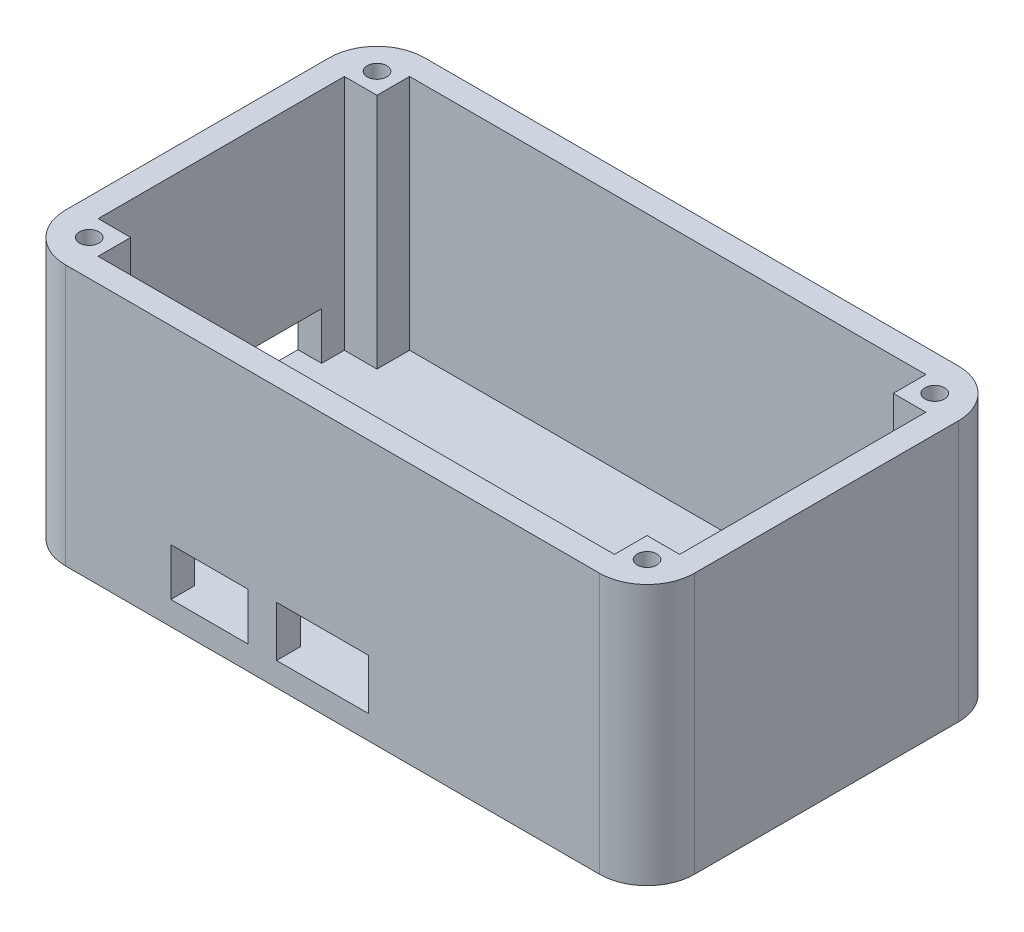
SolidWorks part; units mm, degrees
ref_plane "Front Plane" through (0, 0, 0) normal (0, 0, 1) x (1, 0, 0)
ref_plane "Top Plane" through (0, 0, 0) normal (0, 1, 0) x (1, 0, 0)
ref_plane "Right Plane" through (0, 0, 0) normal (1, 0, 0) x (0, 0, -1)
sketch "Sketch1" plane through (0, 0, 0) normal (0, 1, 0) x (1, 0, 0)
  line L1 (-1.7832, 23.2124) -> (50.2168, 23.2124) construction
  line L2 (-1.7832, 23.2124) -> (-1.7832, 44.2124) construction
  line L3 (-1.7832, 44.2124) -> (50.2168, 44.2124) construction
  line L4 (50.2168, 23.2124) -> (50.2168, 44.2124) construction
  line L9 (34.604, 19.4178) -> (50.604, 19.4178) construction
  line L10 (34.604, 19.4178) -> (34.604, 3.4178) construction
  line L11 (34.604, 3.4178) -> (50.604, 3.4178) construction
  line L12 (50.604, 19.4178) -> (50.604, 3.4178) construction
  line L17 (57.0824, 20.2838) -> (87.0824, 20.2838) construction
  line L22 (57.0824, 20.2838) -> (57.0824, 0.2838) construction
  line L23 (57.0824, 0.2838) -> (87.0824, 0.2838) construction
  line L24 (87.0824, 20.2838) -> (87.0824, 0.2838) construction
  line L25 (8.7723, 20.5931) -> (32.7723, 20.5931) construction
  line L26 (8.7723, 20.5931) -> (8.7723, 2.5931) construction
  line L27 (8.7723, 2.5931) -> (32.7723, 2.5931) construction
  line L28 (32.7723, 20.5931) -> (32.7723, 2.5931) construction
  line L60 (94.1, 48.54) -> (94.1, 0) construction
  line L61 (94.1, 0) -> (0, 0) construction
  line L62 (0, 0) -> (0, 48.54) construction
  line L65 (47.05, 48.54) -> (47.05, 22.7833) construction
  line L66 (-2, 45.04) -> (3.5, 45.04)
  line L67 (3.5, 45.04) -> (3.5, 50.54)
  line L69 (0, 24.27) -> (25.5126, 24.27) construction
  line L78 (2, 54.54) -> (92.1, 54.54)
  line L79 (-6, 46.54) -> (-6, 2)
  line L80 (2, -6) -> (92.1, -6)
  line L81 (100.1, 46.54) -> (100.1, 2)
  line L82 (5.6569, 48.54) -> (94.1, 48.54) construction
  line L84 (-2, 3.5) -> (3.5, 3.5)
  line L85 (3.5, 3.5) -> (3.5, -2)
  line L86 (96.1, 45.04) -> (96.1, 3.5)
  line L87 (90.6, -2) -> (3.5, -2)
  line L88 (96.1, 3.5) -> (90.6, 3.5)
  line L89 (90.6, 3.5) -> (90.6, -2)
  line L90 (96.1, 45.04) -> (90.6, 45.04)
  line L91 (90.6, 45.04) -> (90.6, 50.54)
  line L92 (-2, 3.5) -> (-2, 45.04)
  line L93 (3.5, 50.54) -> (90.6, 50.54)
  circle A26 centre (0, 48.54) radius 1.65
  circle A27 centre (0, 0) radius 1.65
  circle A28 centre (94.1, 48.54) radius 1.65
  circle A29 centre (94.1, 0) radius 1.65
  arc A30 (92.1, 54.54) -> (100.1, 46.54) centre (92.1, 46.54) cw
  arc A31 (92.1, -6) -> (100.1, 2) centre (92.1, 2) ccw
  arc A32 (-6, 2) -> (2, -6) centre (2, 2) ccw
  arc A33 (2, 54.54) -> (-6, 46.54) centre (2, 46.54) ccw
  dimension "D9" = 4
  dimension "D10" = 3.3
  dimension "D16" = 4
  dimension "D3" = 94.1
  dimension "D8" = 3.5
  dimension "D4" = 48.54
  dimension "D11" = 3.3
  dimension "D12" = 3.3
  dimension "D13" = 3.3
  dimension "D18" = 8
  dimension "D5" = 16
  dimension "D6" = 16
  dimension "D7" = 24
  dimension "D14" = 5.5
  dimension "D15" = 4
  dimension "D17" = 4
  dimension "D19" = 5.5
  dimension "D20" = 3.5
  dimension "D21" = 18
  dimension "D22" = 30
  dimension "D23" = 20
  dimension "D24" = 21
  dimension "D25" = 3.5
  dimension "D26" = 52
extrude "Boss-Extrude1" add sketch "Sketch1" along normal blind 40
sketch "Sketch2" plane through (0, 0, 0) normal (0, -1, 0) x (1, 0, 0)
  line L8 (100.1, -46.54) -> (100.1, -2) construction
  line L9 (2, -54.54) -> (92.1, -54.54) construction
  line L10 (-6, -46.54) -> (-6, -2) construction
  line L11 (2, 6) -> (92.1, 6) construction
  line L12 (100.1, -46.54) -> (100.1, -2)
  line L13 (2, -54.54) -> (92.1, -54.54)
  line L14 (-6, -46.54) -> (-6, -2)
  line L15 (2, 6) -> (92.1, 6)
  circle A0 centre (94.1, 0) radius 1.65 construction
  circle A1 centre (94.1, -48.54) radius 1.65 construction
  circle A2 centre (0, -48.54) radius 1.65 construction
  circle A3 centre (0, 0) radius 1.65 construction
  circle A4 centre (94.1, 0) radius 1.65
  circle A5 centre (94.1, -48.54) radius 1.65
  circle A6 centre (0, -48.54) radius 1.65
  circle A7 centre (0, 0) radius 1.65
  arc A8 (100.1, -2) -> (92.1, 6) centre (92.1, -2) ccw construction
  arc A9 (92.1, -54.54) -> (100.1, -46.54) centre (92.1, -46.54) ccw construction
  arc A10 (-6, -46.54) -> (2, -54.54) centre (2, -46.54) ccw construction
  arc A11 (2, 6) -> (-6, -2) centre (2, -2) ccw construction
  arc A12 (100.1, -2) -> (92.1, 6) centre (92.1, -2) ccw
  arc A13 (92.1, -54.54) -> (100.1, -46.54) centre (92.1, -46.54) ccw
  arc A14 (-6, -46.54) -> (2, -54.54) centre (2, -46.54) ccw
  arc A15 (2, 6) -> (-6, -2) centre (2, -2) ccw
extrude "Boss-Extrude2" add sketch "Sketch2" along normal blind 4
sketch "Sketch3" plane through (0, 0, 6) normal (0, 0, 1) x (1, 0, 0)
  line L6 (2, 0) -> (92.1, 0) construction
  line L7 (37.604, 8.5) -> (53.104, 8.5)
  line L8 (37.604, 8.5) -> (37.604, 0)
  line L9 (37.604, 0) -> (53.104, 0)
  line L10 (53.104, 8.5) -> (53.104, 0)
  point P5 (34.604, 0)
  point P9 (13.936, 22.3331)
  dimension "D1" = 15.5
  dimension "D2" = 8.5
  dimension "D3" = 0
  dimension "D4" = 3
extrude "Cut-Extrude1" cut sketch "Sketch3" against normal blind 4
sketch "Sketch5" plane through (-6, 0, 0) normal (-1, 0, 0) x (0, 0, 1)
  line L0 (-45.04, 0) -> (-3.5, 0) construction
  line L1 (-41.2124, 0) -> (-28.2124, 0)
  line L2 (-41.2124, 0) -> (-41.2124, 8)
  line L3 (-41.2124, 8) -> (-28.2124, 8)
  line L4 (-28.2124, 0) -> (-28.2124, 8)
  point P6 (-44.2124, 0)
  dimension "D1" = 13
  dimension "D2" = 8
  dimension "D3" = 3
extrude "Cut-Extrude2" cut sketch "Sketch5" against normal blind 4
sketch "Sketch6" plane through (0, 0, 6) normal (0, 0, 1) x (1, 0, 0)
  line L0 (3.5, 0) -> (90.6, 0) construction
  line L1 (32.7723, 0) -> (19.7723, 0)
  line L2 (32.7723, 0) -> (32.7723, 8)
  line L3 (32.7723, 8) -> (19.7723, 8)
  line L4 (19.7723, 0) -> (19.7723, 8)
  point P6 (32.7723, 0)
  dimension "D1" = 13
  dimension "D2" = 8
  dimension "D3" = 0
extrude "Cut-Extrude3" cut sketch "Sketch6" against normal blind 4
